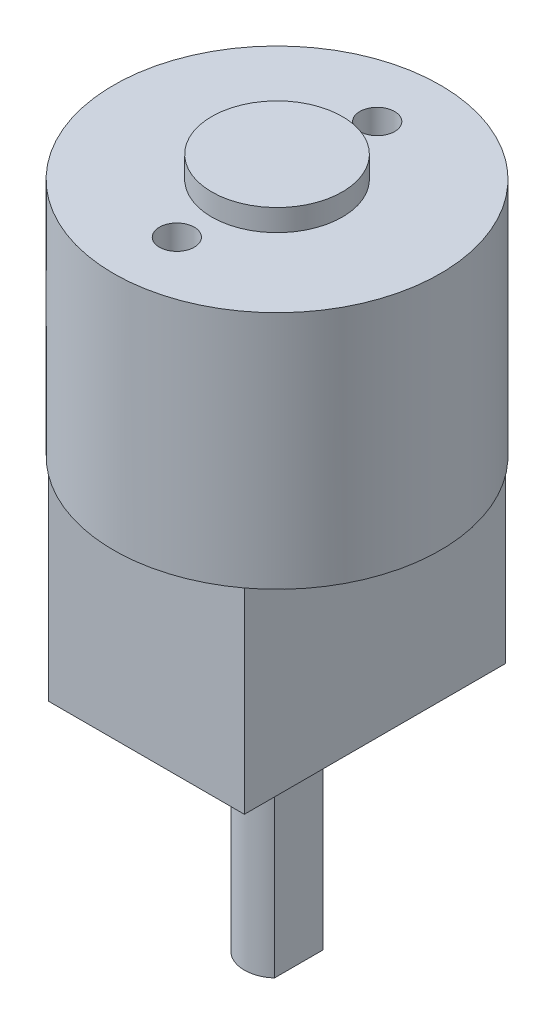
SolidWorks part; units mm, degrees
ref_plane "Front Plane" through (0, 0, 0) normal (0, 0, 1) x (1, 0, 0)
ref_plane "Top Plane" through (0, 0, 0) normal (0, 1, 0) x (1, 0, 0)
ref_plane "Right Plane" through (0, 0, 0) normal (1, 0, 0) x (0, 0, -1)
sketch "Sketch1" plane through (0, 0, 0) normal (0, 1, 0) x (1, 0, 0)
  circle A0 centre (0, 0) radius 7.5
  dimension "D1" = 15
extrude "Boss-Extrude1" add sketch "Sketch1" along normal blind 11
sketch "Sketch2" plane through (0, 11, 0) normal (0, 1, 0) x (1, 0, 0)
  circle A0 centre (0, 0) radius 3
  dimension "D1" = 6
extrude "Boss-Extrude2" add sketch "Sketch2" along normal blind 1
sketch "Sketch3" plane through (0, 0, 0) normal (0, -1, 0) x (1, 0, 0)
  line L1 (-4.5, 6) -> (4.5, 6)
  line L2 (-4.5, 6) -> (-4.5, -6)
  line L3 (-4.5, -6) -> (4.5, -6)
  line L4 (4.5, 6) -> (4.5, -6)
  line L5 (0, -6) -> (0, 6) construction
  line L6 (-4.5, 0) -> (4.5, 0) construction
  circle A0 centre (0, 0) radius 7.5 construction
  point P6 (0, 0)
  point P356 (0, 0)
  dimension "D1" = 12
extrude "Boss-Extrude3" add sketch "Sketch3" along normal blind 9
sketch "Sketch4" plane through (0, -9, 0) normal (0, -1, 0) x (1, 0, 0)
  circle A0 centre (0, 0) radius 2
  dimension "D1" = 4
extrude "Boss-Extrude4" add sketch "Sketch4" along normal blind 0.7
sketch "Sketch5" plane through (0, -9.7, 0) normal (0, -1, 0) x (1, 0, 0)
  circle A0 centre (0, 0) radius 1.5
  dimension "D1" = 3
extrude "Boss-Extrude5" add sketch "Sketch5" along normal blind 10
sketch "Sketch6" plane through (0, -19.7, 0) normal (0, -1, 0) x (1, 0, 0)
  line L0 (1, 1.118) -> (1, -1.118)
  circle A2 centre (0, 0) radius 1.5
  circle A3 centre (0, 0) radius 1.5
  circle M4 centre (0, 0) radius 1.5
  dimension "D1" = 0
  dimension "D2" = 1
extrude "Cut-Extrude1" cut sketch "Sketch6" against normal blind 10 contours L0 M4
sketch "Sketch7" plane through (0, -9, 0) normal (0, -1, 0) x (1, 0, 0)
  line L0 (0, 4.5) -> (0, 0) construction
  line L1 (0, 0) -> (0, -4.5) construction
  circle A0 centre (0, 4.5) radius 0.8
  circle A1 centre (0, -4.5) radius 0.8
  dimension "D1" = 1.6
  dimension "D2" = 4.5
  dimension "D3" = 4.5
extrude "Cut-Extrude2" cut sketch "Sketch7" against normal blind 5
sketch "Sketch8" plane through (0, 11, 0) normal (0, 1, 0) x (1, 0, 0)
  circle A0 centre (0, 0) radius 4.6 construction
  circle A1 centre (0, 4.6) radius 0.8
  circle A2 centre (0, -4.6) radius 0.8
  dimension "D1" = 9.2
  dimension "D2" = 1.6
extrude "Cut-Extrude3" cut sketch "Sketch8" against normal blind 5
